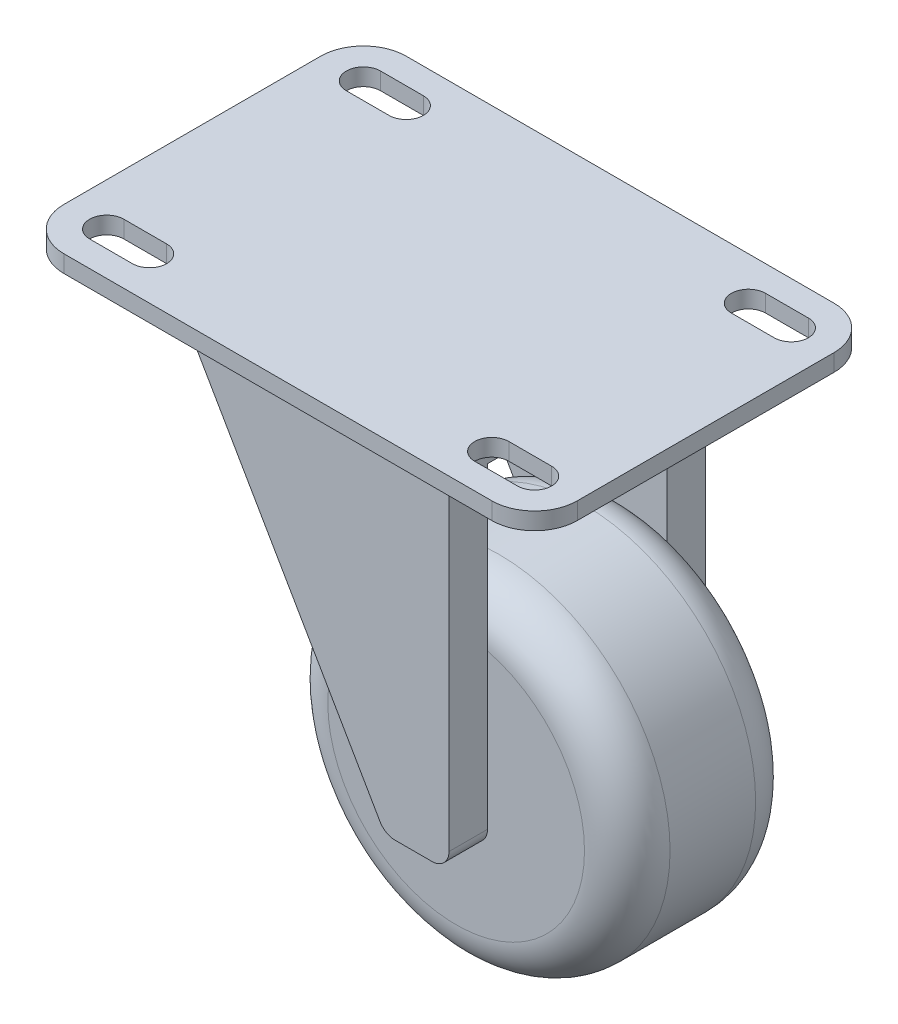
SolidWorks part; units mm, degrees
ref_plane "Front Plane" through (0, 0, 0) normal (0, 0, 1) x (1, 0, 0)
ref_plane "Top Plane" through (0, 0, 0) normal (0, 1, 0) x (1, 0, 0)
ref_plane "Right Plane" through (0, 0, 0) normal (1, 0, 0) x (0, 0, -1)
sketch "Sketch1" plane through (0, 0, 0) normal (0, 1, 0) x (1, 0, 0)
  line L1 (25, -20) -> (-25, -20)
  line L2 (30, -15) -> (30, 15)
  line L3 (25, 20) -> (-25, 20)
  line L4 (-30, -15) -> (-30, 15)
  line L5 (30, -20) -> (-30, 20) construction
  line L6 (30, 20) -> (-30, -20) construction
  arc A0 (-25, -20) -> (-30, -15) centre (-25, -15) cw
  arc A1 (25, -20) -> (30, -15) centre (25, -15) ccw
  arc A2 (30, 15) -> (25, 20) centre (25, 15) ccw
  arc A3 (-25, 20) -> (-30, 15) centre (-25, 15) ccw
  point P0 (0, 0)
  dimension "D3" = 5
  dimension "D1" = 60
  dimension "D2" = 40
extrude "Boss-Extrude1" add sketch "Sketch1" along normal blind 2
sketch "Sketch2" plane through (0, 2, 0) normal (0, 1, 0) x (1, 0, 0)
  line L0 (-25, 15) -> (-20, 15) construction
  line L1 (-25, 17) -> (-20, 17)
  line L2 (-25, 13) -> (-20, 13)
  line L3 (0, -55) -> (0, 55) construction
  line L4 (25, 15) -> (20, 15) construction
  line L5 (25, 17) -> (20, 17)
  line L6 (25, 13) -> (20, 13)
  line L7 (-55, 0) -> (55, 0) construction
  line L8 (25, -15) -> (20, -15) construction
  line L9 (25, -17) -> (20, -17)
  line L10 (25, -13) -> (20, -13)
  line L11 (-25, -15) -> (-20, -15) construction
  line L12 (-25, -17) -> (-20, -17)
  line L13 (-25, -13) -> (-20, -13)
  arc A0 (-25, 17) -> (-25, 13) centre (-25, 15) ccw
  arc A1 (-20, 13) -> (-20, 17) centre (-20, 15) ccw
  arc A2 (25, 17) -> (25, 13) centre (25, 15) cw
  arc A3 (20, 13) -> (20, 17) centre (20, 15) cw
  arc A4 (25, -17) -> (25, -13) centre (25, -15) ccw
  arc A5 (20, -13) -> (20, -17) centre (20, -15) ccw
  arc A6 (-25, -17) -> (-25, -13) centre (-25, -15) cw
  arc A7 (-20, -13) -> (-20, -17) centre (-20, -15) cw
  point P2 (-22.5, 15)
  point P12 (22.5, 15)
  point P21 (22.5, -15)
  point P28 (-22.5, -15)
  dimension "D1" = 2
  dimension "D2" = 5
  dimension "D3" = 22.5
  dimension "D4" = 15
extrude "Cut-Extrude1" cut sketch "Sketch2" against normal blind 2
sketch "Sketch3" plane through (0, 0, 0) normal (0, -1, 0) x (1, 0, 0)
  circle A0 centre (0, 0) radius 12
extrude "Boss-Extrude2" add sketch "Sketch3" along normal blind 2
sketch "Sketch4" plane through (0, -2, 0) normal (0, -1, 0) x (1, 0, 0)
  line L1 (15, -15) -> (-15, -15)
  line L2 (15, -15) -> (15, 15)
  line L3 (15, 15) -> (-15, 15)
  line L4 (-15, -15) -> (-15, 15)
  line L5 (15, -15) -> (-15, 15) construction
  line L6 (15, 15) -> (-15, -15) construction
  point P0 (0, 0)
  dimension "D1" = 30
  dimension "D2" = 30
extrude "Boss-Extrude3" add sketch "Sketch4" along normal blind 2
sketch "Sketch5" plane through (0, 0, 15) normal (0, 0, 1) x (1, 0, 0)
  line L0 (-15, -4) -> (6.9393, -42)
  line L1 (-15, -4) -> (15, -4)
  line L2 (15, -4) -> (15, -41)
  line L3 (13, -43) -> (8.6714, -43)
  line L4 (-15, -4) -> (15, -4)
  line L5 (-25, 2) -> (25, 2) construction
  circle A0 centre (10.8357, -38) radius 2
  arc A1 (13, -43) -> (15, -41) centre (13, -41) ccw
  arc A2 (8.6714, -43) -> (6.9393, -42) centre (8.6714, -41) cw
  point P10 (10.8357, -43)
  line M6 (-15, -4) -> (15, -4)
  dimension "D3" = 5
  dimension "D5" = 2
  dimension "D1" = 60
  dimension "D2" = 45
  dimension "D4" = 0
extrude "Boss-Extrude4" add sketch "Sketch5" against normal blind 4.5 contours L3 L2 L0 A0 M6
mirror "Mirror1" about plane through (0, 0, 0) normal (0, 0, 1) of "Boss-Extrude4"
sketch "Sketch6" plane through (0, 0, 15) normal (0, 0, 1) x (1, 0, 0)
  circle A0 centre (10.8357, -38) radius 2
extrude "Boss-Extrude5" add sketch "Sketch6" against normal blind 30
sketch "Sketch7" plane through (0, 0, 0) normal (0, 0, 1) x (1, 0, 0)
  circle A0 centre (10.8357, -38) radius 20
extrude "Boss-Extrude6" add sketch "Sketch7" along normal mid plane 20
fillet "Fillet1" radius 5 2 edges at (30.8357, -38, -10) (30.8357, -38, 10)
